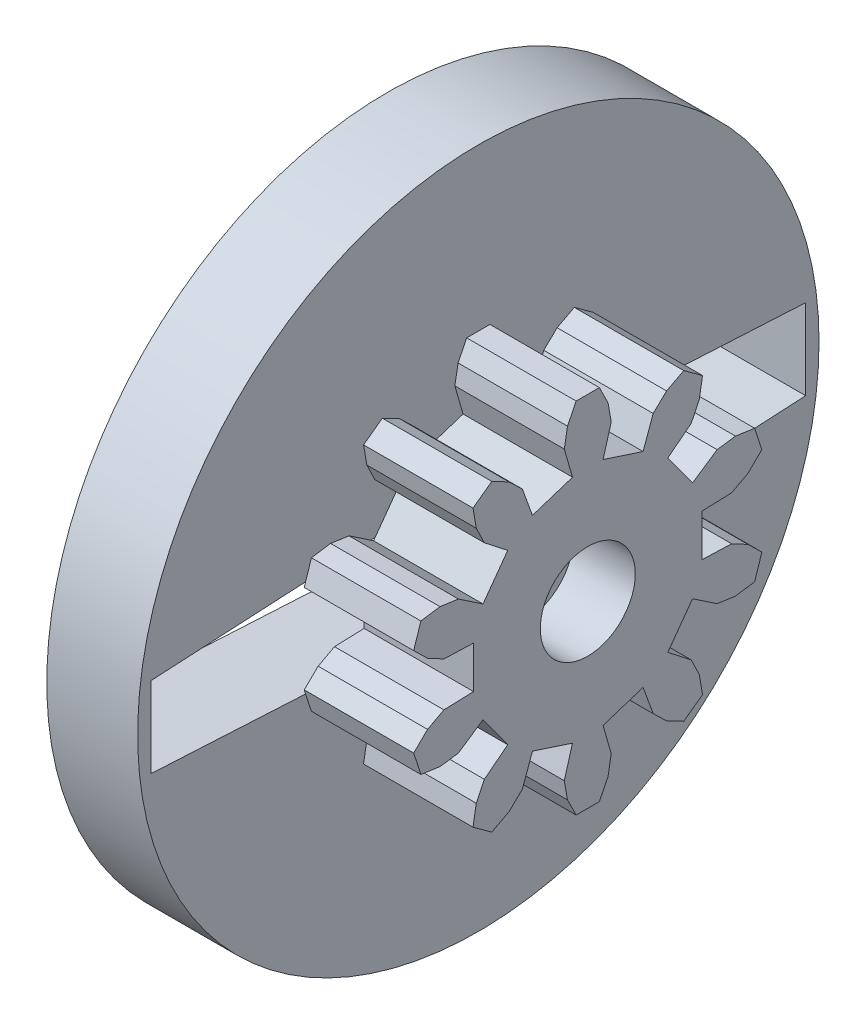
SolidWorks part; units mm, degrees
ref_plane "Front Plane" through (0, 0, 0) normal (0, 0, 1) x (1, 0, 0)
ref_plane "Top Plane" through (0, 0, 0) normal (0, 1, 0) x (1, 0, 0)
ref_plane "Right Plane" through (0, 0, 0) normal (1, 0, 0) x (0, 0, -1)
ref_plane "Plane1" through (204.9, 0, 0) normal (1, 0, 0) x (0, 0, -1)
ref_plane "Plane2" through (209.3, 0, 0) normal (1, 0, 0) x (0, 0, -1)
ref_plane "Plane3" through (214.6, 0, 0) normal (1, 0, 0) x (0, 0, -1)
sketch "Sketch1" plane through (204.9, 0, 0) normal (1, 0, 0) x (0, 0, -1)
  circle A0 centre (-301, 0) radius 16.5
extrude "Boss-Extrude1" add sketch "Sketch1" along normal blind 4.4
sketch "Sketch2" plane through (209.3, 0, 0) normal (1, 0, 0) x (0, 0, -1)
  line L0 (-306.532, 1.019) -> (-307.966, 1.068)
  line L1 (-307.966, 1.068) -> (-308.758, 1.491)
  line L2 (-308.758, 1.491) -> (-309.431, 2.148)
  line L3 (-309.431, 2.148) -> (-309.083, 3.218)
  line L4 (-309.083, 3.218) -> (-308.153, 3.354)
  line L5 (-308.153, 3.354) -> (-307.264, 3.23)
  line L6 (-307.264, 3.23) -> (-306.074, 2.427)
  line L7 (-306.074, 2.427) -> (-304.876, 4.076)
  line L8 (-304.876, 4.076) -> (-306.008, 4.959)
  line L9 (-306.008, 4.959) -> (-306.4, 5.766)
  line L10 (-306.4, 5.766) -> (-306.558, 6.693)
  line L11 (-306.558, 6.693) -> (-305.648, 7.354)
  line L12 (-305.648, 7.354) -> (-304.815, 6.918)
  line L13 (-304.815, 6.918) -> (-304.169, 6.295)
  line L14 (-304.169, 6.295) -> (-303.679, 4.946)
  line L15 (-303.679, 4.946) -> (-301.74, 5.576)
  line L16 (-301.74, 5.576) -> (-302.137, 6.955)
  line L17 (-302.137, 6.955) -> (-301.98, 7.839)
  line L18 (-301.98, 7.839) -> (-301.563, 8.682)
  line L19 (-301.563, 8.682) -> (-300.437, 8.682)
  line L20 (-300.437, 8.682) -> (-300.02, 7.839)
  line L21 (-300.02, 7.839) -> (-299.863, 6.955)
  line L22 (-299.863, 6.955) -> (-300.26, 5.576)
  line L23 (-300.26, 5.576) -> (-298.321, 4.946)
  line L24 (-298.321, 4.946) -> (-297.831, 6.295)
  line L25 (-297.831, 6.295) -> (-297.185, 6.918)
  line L26 (-297.185, 6.918) -> (-296.352, 7.354)
  line L27 (-296.352, 7.354) -> (-295.442, 6.693)
  line L28 (-295.442, 6.693) -> (-295.6, 5.766)
  line L29 (-295.6, 5.766) -> (-295.992, 4.959)
  line L30 (-295.992, 4.959) -> (-297.124, 4.076)
  line L31 (-297.124, 4.076) -> (-295.926, 2.427)
  line L32 (-295.926, 2.427) -> (-294.736, 3.23)
  line L33 (-294.736, 3.23) -> (-293.847, 3.354)
  line L34 (-293.847, 3.354) -> (-292.917, 3.218)
  line L35 (-292.917, 3.218) -> (-292.569, 2.148)
  line L36 (-292.569, 2.148) -> (-293.242, 1.491)
  line L37 (-293.242, 1.491) -> (-294.034, 1.068)
  line L38 (-294.034, 1.068) -> (-295.468, 1.019)
  line L39 (-295.468, 1.019) -> (-295.468, -1.019)
  line L40 (-295.468, -1.019) -> (-294.034, -1.068)
  line L41 (-294.034, -1.068) -> (-293.242, -1.491)
  line L42 (-293.242, -1.491) -> (-292.569, -2.148)
  line L43 (-292.569, -2.148) -> (-292.917, -3.218)
  line L44 (-292.917, -3.218) -> (-293.847, -3.354)
  line L45 (-293.847, -3.354) -> (-294.736, -3.23)
  line L46 (-294.736, -3.23) -> (-295.926, -2.427)
  line L47 (-295.926, -2.427) -> (-297.124, -4.076)
  line L48 (-297.124, -4.076) -> (-295.992, -4.959)
  line L49 (-295.992, -4.959) -> (-295.6, -5.766)
  line L50 (-295.6, -5.766) -> (-295.442, -6.693)
  line L51 (-295.442, -6.693) -> (-296.352, -7.354)
  line L52 (-296.352, -7.354) -> (-297.185, -6.918)
  line L53 (-297.185, -6.918) -> (-297.831, -6.295)
  line L54 (-297.831, -6.295) -> (-298.321, -4.946)
  line L55 (-298.321, -4.946) -> (-300.26, -5.576)
  line L56 (-300.26, -5.576) -> (-299.863, -6.955)
  line L57 (-299.863, -6.955) -> (-300.02, -7.839)
  line L58 (-300.02, -7.839) -> (-300.437, -8.682)
  line L59 (-300.437, -8.682) -> (-301.563, -8.682)
  line L60 (-301.563, -8.682) -> (-301.98, -7.839)
  line L61 (-301.98, -7.839) -> (-302.137, -6.955)
  line L62 (-302.137, -6.955) -> (-301.74, -5.576)
  line L63 (-301.74, -5.576) -> (-303.679, -4.946)
  line L64 (-303.679, -4.946) -> (-304.169, -6.295)
  line L65 (-304.169, -6.295) -> (-304.815, -6.918)
  line L66 (-304.815, -6.918) -> (-305.648, -7.354)
  line L67 (-305.648, -7.354) -> (-306.558, -6.693)
  line L68 (-306.558, -6.693) -> (-306.4, -5.766)
  line L69 (-306.4, -5.766) -> (-306.008, -4.959)
  line L70 (-306.008, -4.959) -> (-304.876, -4.076)
  line L71 (-304.876, -4.076) -> (-306.074, -2.427)
  line L72 (-306.074, -2.427) -> (-307.264, -3.23)
  line L73 (-307.264, -3.23) -> (-308.153, -3.354)
  line L74 (-308.153, -3.354) -> (-309.083, -3.218)
  line L75 (-309.083, -3.218) -> (-309.431, -2.148)
  line L76 (-309.431, -2.148) -> (-308.758, -1.491)
  line L77 (-308.758, -1.491) -> (-307.966, -1.068)
  line L78 (-307.966, -1.068) -> (-306.532, -1.019)
  line L79 (-306.532, -1.019) -> (-306.532, 1.019)
extrude "Boss-Extrude2" add sketch "Sketch2" along normal blind 5.3
sketch "Sketch3" plane through (204.9, 0, 0) normal (1, 0, 0) x (0, 0, -1)
  circle A0 centre (-301, 0) radius 3.6
extrude "Cut-Extrude1" cut sketch "Sketch3" along normal blind 4.4
sketch "Sketch4" plane through (204.9, 0, 0) normal (1, 0, 0) x (0, 0, -1)
  line L0 (-285.15, -1.95) -> (-301, -2.8)
  line L1 (-301, -2.8) -> (-316.85, -1.95)
  line L2 (-316.85, -1.95) -> (-316.85, 1.95)
  line L3 (-316.85, 1.95) -> (-301, 2.8)
  line L4 (-301, 2.8) -> (-285.15, 1.95)
  line L5 (-285.15, 1.95) -> (-285.15, -1.95)
extrude "Cut-Extrude2" cut sketch "Sketch4" along normal blind 4.4
sketch "Sketch5" plane through (204.9, 0, 0) normal (1, 0, 0) x (0, 0, -1)
  circle A0 centre (-301, 0) radius 1.2
extrude "Cut-Extrude3" cut sketch "Sketch5" along normal through all
sketch "Sketch6" plane through (214.6, 0, 0) normal (1, 0, 0) x (0, 0, -1)
  circle A0 centre (-301, 0) radius 2.3
extrude "Cut-Extrude4" cut sketch "Sketch6" against normal blind 3
